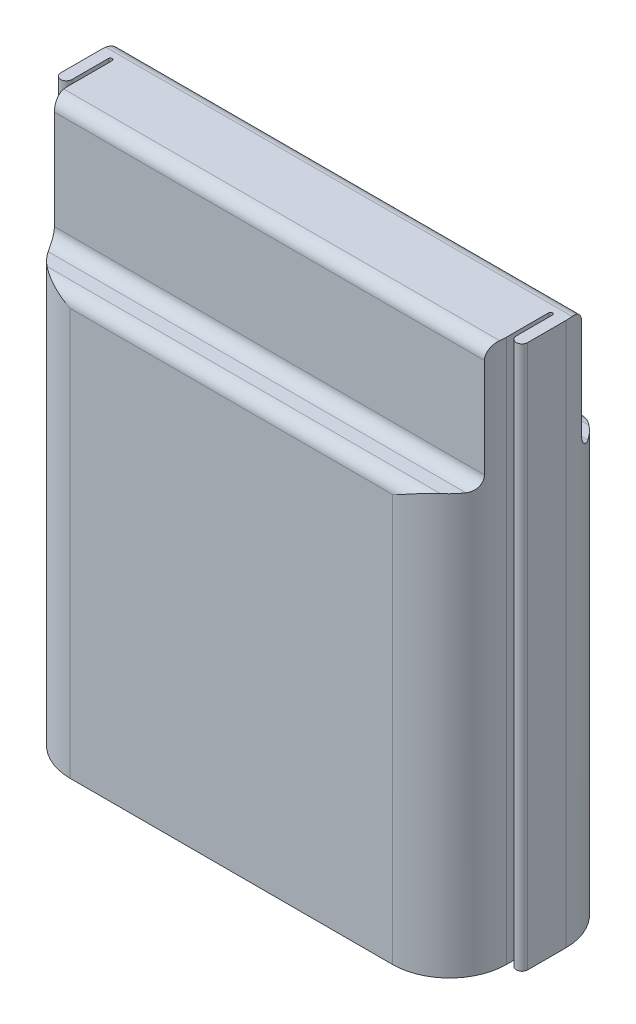
SolidWorks part; units mm, degrees
ref_plane "Front" through (0, 0, 0) normal (0, 0, 1) x (1, 0, 0)
ref_plane "Top" through (0, 0, 0) normal (0, 1, 0) x (1, 0, 0)
ref_plane "Right" through (0, 0, 0) normal (1, 0, 0) x (0, 0, -1)
sketch "Эскиз1" plane through (0, 0, 0) normal (0, 1, 0) x (1, 0, 0)
  line L0 (-9.25, 0) -> (9.25, 0)
  line L1 (-8.45, -8.3) -> (8.45, -8.3)
  line L2 (-12.25, -3) -> (-12.25, -5)
  line L3 (12.25, -3) -> (12.25, -5)
  line L4 (-11.45, -5.3) -> (-11.45, -3.1)
  line L5 (11.45, -3.1) -> (11.45, -5.3)
  line L6 (11.65, -5) -> (11.65, -3.1)
  line L7 (-11.65, -5) -> (-11.65, -3.1)
  arc A0 (-9.25, 0) -> (-12.25, -3) centre (-9.25, -3) ccw
  arc A1 (9.25, 0) -> (12.25, -3) centre (9.25, -3) cw
  arc A2 (-11.45, -5.3) -> (-8.45, -8.3) centre (-8.45, -5.3) ccw
  arc A3 (11.45, -5.3) -> (8.45, -8.3) centre (8.45, -5.3) cw
  arc A4 (12.25, -5) -> (11.65, -5) centre (11.95, -5) cw
  arc A5 (11.45, -3.1) -> (11.65, -3.1) centre (11.55, -3.1) cw
  arc A6 (-12.25, -5) -> (-11.65, -5) centre (-11.95, -5) ccw
  arc A7 (-11.45, -3.1) -> (-11.65, -3.1) centre (-11.55, -3.1) ccw
  point P20 (11.55, -3)
  point P21 (11.95, -5.3)
  point P27 (-11.55, -3)
  point P28 (-11.95, -5.3)
  dimension "D1" = 24.5
  dimension "D3" = 3
  dimension "D4" = 3
  dimension "D5" = 0.3
  dimension "D6" = 0.1
  dimension "D2" = 8.3
extrude "Бобышка-Вытянуть1" add sketch "Эскиз1" along normal mid plane 28.5
sketch "Эскиз2" plane through (0, 0, 0) normal (1, 0, 0) x (0, 0, -1)
  line L0 (-6.3, 13.6) -> (-6.3, 8.4)
  line L1 (-6.95, 7.75) -> (-7.65, 7.75)
  line L2 (-8.3, 14.25) -> (-8.3, 7.1)
  line L3 (-8.3, 14.25) -> (-8.3, -14.25) construction
  line L5 (-8.3, 14.25) -> (-8.3, 15.25)
  line L6 (-8.3, 14.25) -> (-5.65, 14.25) construction
  line L7 (0, 14.25) -> (-3, 14.25) construction
  line L8 (-8.3, 15.25) -> (0, 15.25)
  line L9 (0, 15.25) -> (0, 7.1)
  line L10 (-0.65, 7.75) -> (-1.35, 7.75)
  line L11 (-2, 8.4) -> (-2, 13.6)
  line L12 (-2.65, 14.25) -> (-5.65, 14.25)
  arc A0 (-6.3, 8.4) -> (-6.95, 7.75) centre (-6.95, 8.4) cw
  arc A1 (-7.65, 7.75) -> (-8.3, 7.1) centre (-7.65, 7.1) ccw
  arc A2 (-5.65, 14.25) -> (-6.3, 13.6) centre (-5.65, 13.6) ccw
  arc A3 (0, 7.1) -> (-0.65, 7.75) centre (-0.65, 7.1) ccw
  arc A4 (-1.35, 7.75) -> (-2, 8.4) centre (-1.35, 8.4) cw
  arc A5 (-2, 13.6) -> (-2.65, 14.25) centre (-2.65, 13.6) ccw
  point P27 (-0.65, 7.6141)
  dimension "D1" = 0.65
  dimension "D4" = 2
  dimension "D2" = 1
  dimension "D3" = 6.5
  dimension "D5" = 2
extrude "Вырез-Вытянуть1" cut sketch "Эскиз2" against normal up to next and the other way up to next
